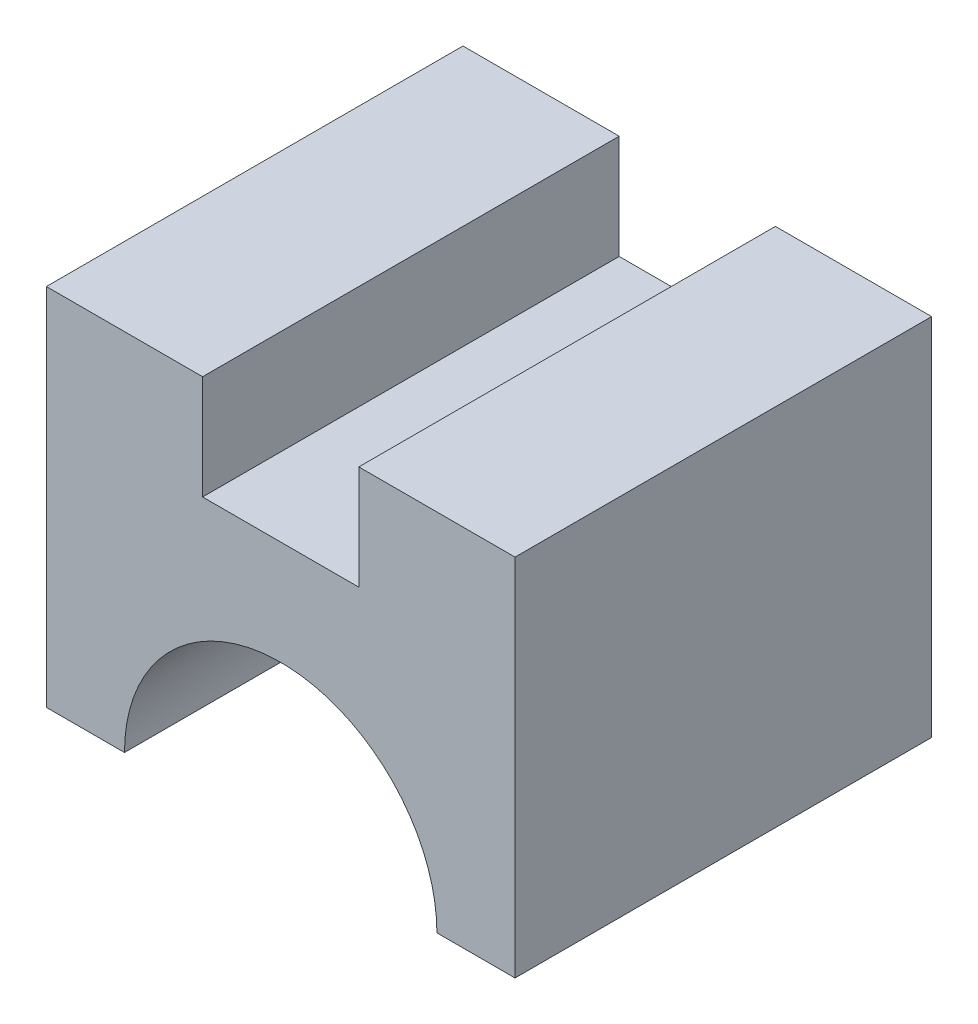
SolidWorks part; units mm, degrees
ref_plane "Front Plane" through (0, 0, 0) normal (0, 0, 1) x (1, 0, 0)
ref_plane "Top Plane" through (0, 0, 0) normal (0, 1, 0) x (1, 0, 0)
ref_plane "Right Plane" through (0, 0, 0) normal (1, 0, 0) x (0, 0, -1)
sketch "Sketch1" plane through (0, 0, 0) normal (0, 0, 1) x (1, 0, 0)
  line L0 (0, 0) -> (0, 381) construction
  line L1 (-381, 0) -> (381, 0) construction
  line L2 (-381, 0) -> (-571.5, 0)
  line L3 (-571.5, 0) -> (-571.5, 889)
  line L4 (-571.5, 889) -> (-190.5, 889)
  line L5 (-190.5, 889) -> (-190.5, 635)
  line L6 (-190.5, 635) -> (190.5, 635)
  line L7 (0, 635) -> (0, 381) construction
  line L8 (381, 0) -> (571.5, 0)
  line L9 (571.5, 0) -> (571.5, 889)
  line L10 (571.5, 889) -> (190.5, 889)
  line L11 (190.5, 889) -> (190.5, 635)
  arc A0 (-381, 0) -> (381, 0) centre (0, 0) cw
  dimension "D1" = 381
  dimension "D2" = 889
  dimension "D3" = 190.5
  dimension "D4" = 381
  dimension "D5" = 254
extrude "Boss-Extrude1" add sketch "Sketch1" along normal blind 1016
